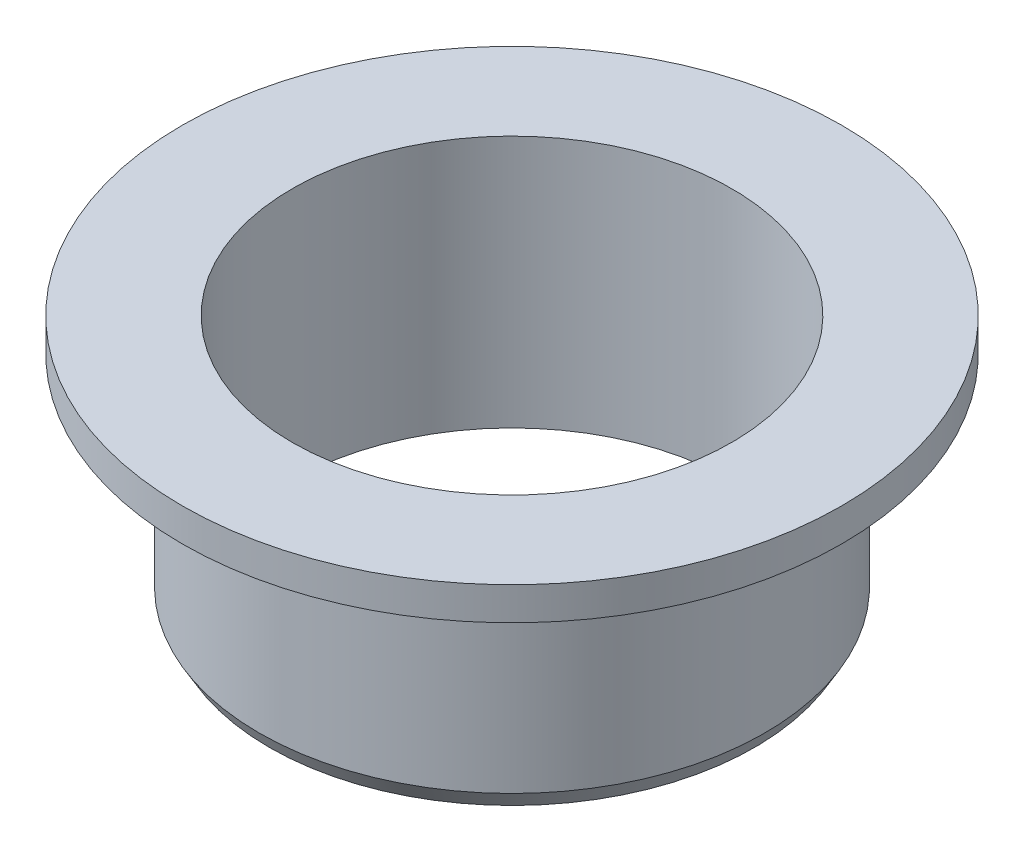
SolidWorks part; units mm, degrees
ref_plane "Front Plane" through (0, 0, 0) normal (0, 0, 1) x (1, 0, 0)
ref_plane "Top Plane" through (0, 0, 0) normal (0, 1, 0) x (1, 0, 0)
ref_plane "Right Plane" through (0, 0, 0) normal (1, 0, 0) x (0, 0, -1)
sketch "Sketch1" plane through (0, 0, 0) normal (0, 0, 1) x (1, 0, 0)
  line L0 (-15, 0) -> (-15, -1.5)
  line L1 (-15, -1.5) -> (-12, -1.5)
  line L2 (-11.5, -2) -> (-11.5, -10.7)
  line L3 (-11.5, -10.7) -> (-11.0381, -11.5)
  line L4 (-11.0381, -11.5) -> (-10, -11.5)
  line L5 (-10, -11.5) -> (-10, 0)
  line L6 (-10, 0) -> (-15, 0)
  line L7 (0, 0) -> (0, -11.7253) construction
  arc A0 (-12, -1.5) -> (-11.5, -2) centre (-12, -2) cw
  dimension "D5" = 0.5
  dimension "D1" = 1.5
  dimension "D2" = 1.5
  dimension "D3" = 0.8
  dimension "D4" = 30
  dimension "D6" = 30
  dimension "D7" = 20
  dimension "D8" = 11.5
revolve "Revolve1" add sketch "Sketch1" angle 360 about L7
